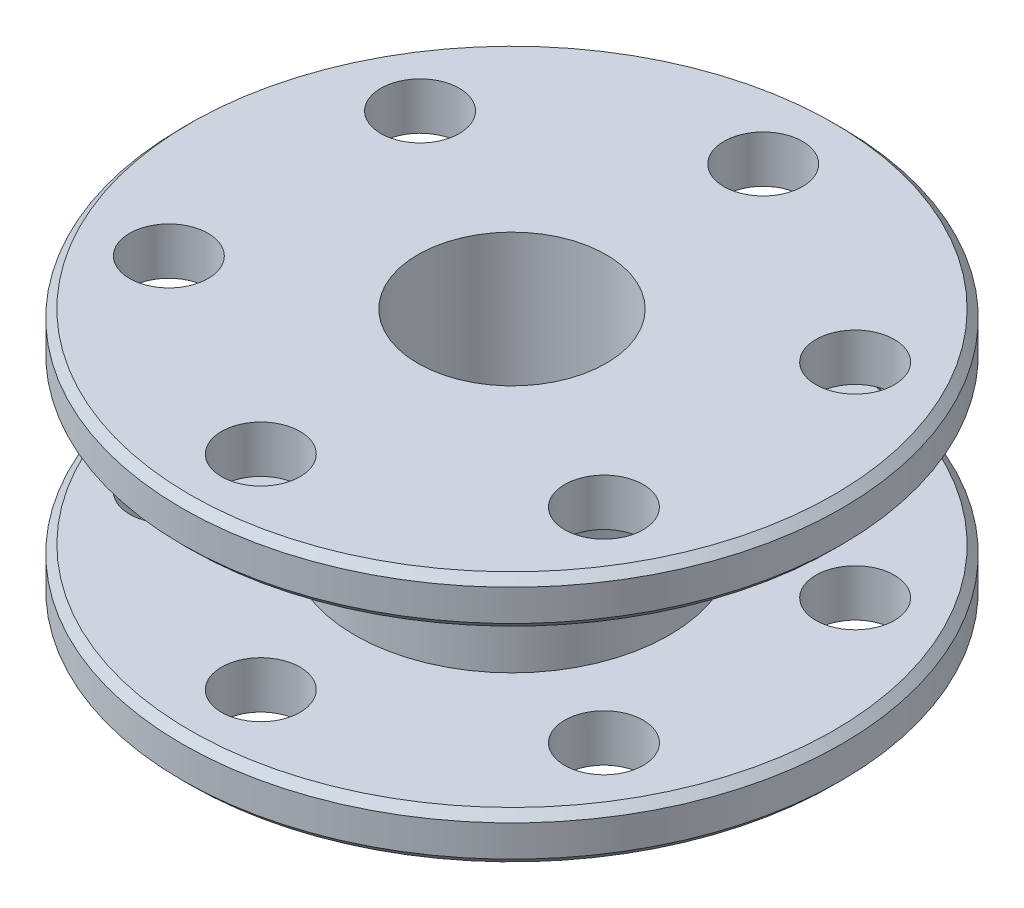
SolidWorks part; units mm, degrees
ref_plane "Front Plane" through (0, 0, 0) normal (0, 0, 1) x (1, 0, 0)
ref_plane "Top Plane" through (0, 0, 0) normal (0, 1, 0) x (1, 0, 0)
ref_plane "Right Plane" through (0, 0, 0) normal (1, 0, 0) x (0, 0, -1)
sketch "Sketch1" plane through (0, 0, 0) normal (0, 1, 0) x (1, 0, 0)
  circle A0 centre (0, 0) radius 21
  circle A1 centre (0, 0) radius 6
  circle A2 centre (0, 0) radius 16 construction
  circle A4 centre (0, 16) radius 2.5
  circle A5 centre (13.8564, 8) radius 2.5
  circle A6 centre (13.8564, -8) radius 2.5
  circle A7 centre (0, -16) radius 2.5
  circle A8 centre (-13.8564, -8) radius 2.5
  circle A9 centre (-13.8564, 8) radius 2.5
  point P20 (0, 0)
  dimension "D1" = 42
  dimension "D2" = 12
  dimension "D3" = 32
  dimension "D4" = 5
  dimension "D5" = 6
extrude "Boss-Extrude1" add sketch "Sketch1" along normal blind 16
sketch "Sketch2" plane through (0, 0, 0) normal (1, 0, 0) x (0, 0, -1)
  line L0 (0, 0) -> (0, 22.0953) construction
  line L1 (18.5, 16) -> (13.5, 16) construction
  line L2 (10, 13) -> (26.3277, 13)
  line L3 (10, 13) -> (10, 3)
  line L4 (10, 3) -> (26.3277, 3)
  line L5 (26.3277, 13) -> (26.3277, 3)
  line L6 (-21, 0) -> (21, 0) construction
  dimension "D1" = 3
  dimension "D2" = 3
  dimension "D3" = 10
revolve "Cut-Revolve1" cut sketch "Sketch2" angle 360 about L0
chamfer "Chamfer1" distance 0.5 angle 45 4 edges at (0, 0, 21) (0, 3, -21) (0, 13, 21) (0, 16, 21)
ref_plane "Plane1" through (0, 8, 0) normal (0, 1, 0) x (1, 0, 0)
